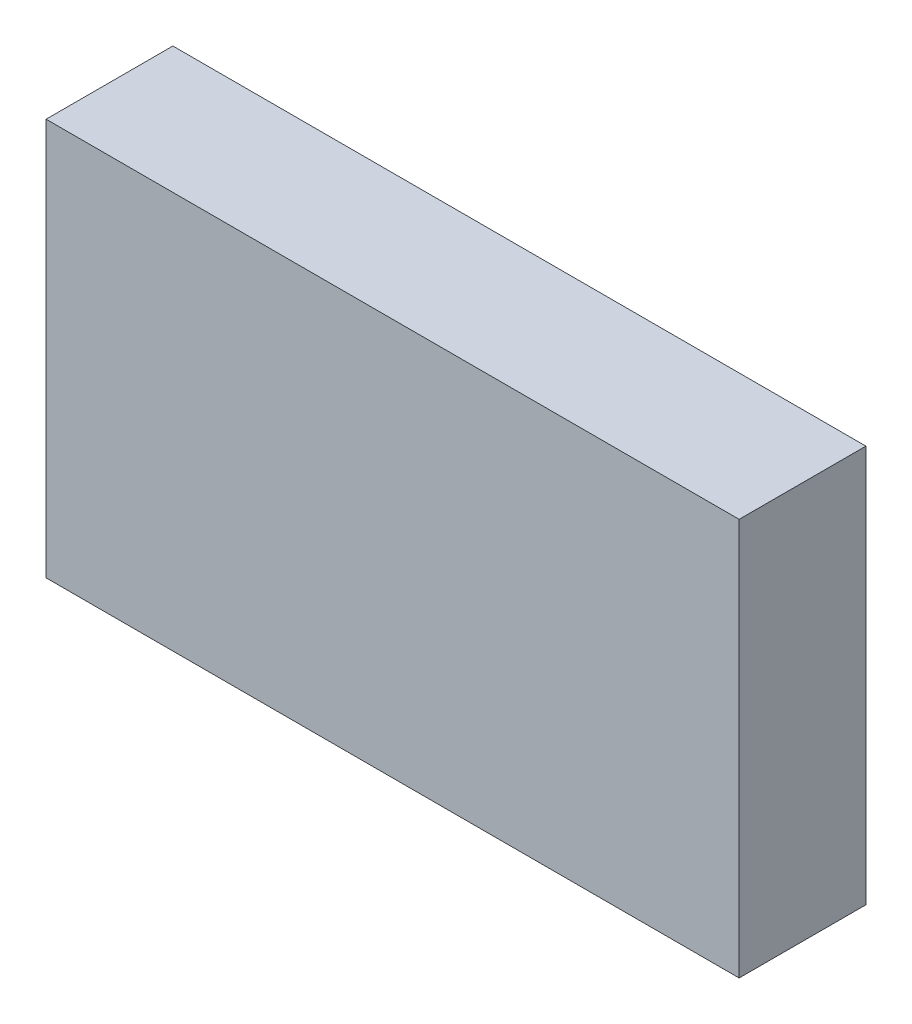
SolidWorks part; units mm, degrees
material "NEOPRENE"
ref_plane "Plan de face" through (0, 0, 0) normal (0, 0, 1) x (1, 0, 0)
ref_plane "Plan de dessus" through (0, 0, 0) normal (0, 1, 0) x (1, 0, 0)
ref_plane "Plan de droite" through (0, 0, 0) normal (1, 0, 0) x (0, 0, -1)
sketch "Esquisse1" plane through (0, 0, 0) normal (0, 0, 1) x (1, 0, 0)
  line L1 (0, 0) -> (16.4, 0)
  line L2 (0, 0) -> (0, 9.4)
  line L3 (0, 9.4) -> (16.4, 9.4)
  line L4 (16.4, 0) -> (16.4, 9.4)
  dimension "D1" = 16.4
  dimension "D2" = 9.4
extrude "Boss.-Extru.1" add sketch "Esquisse1" along normal blind 3
